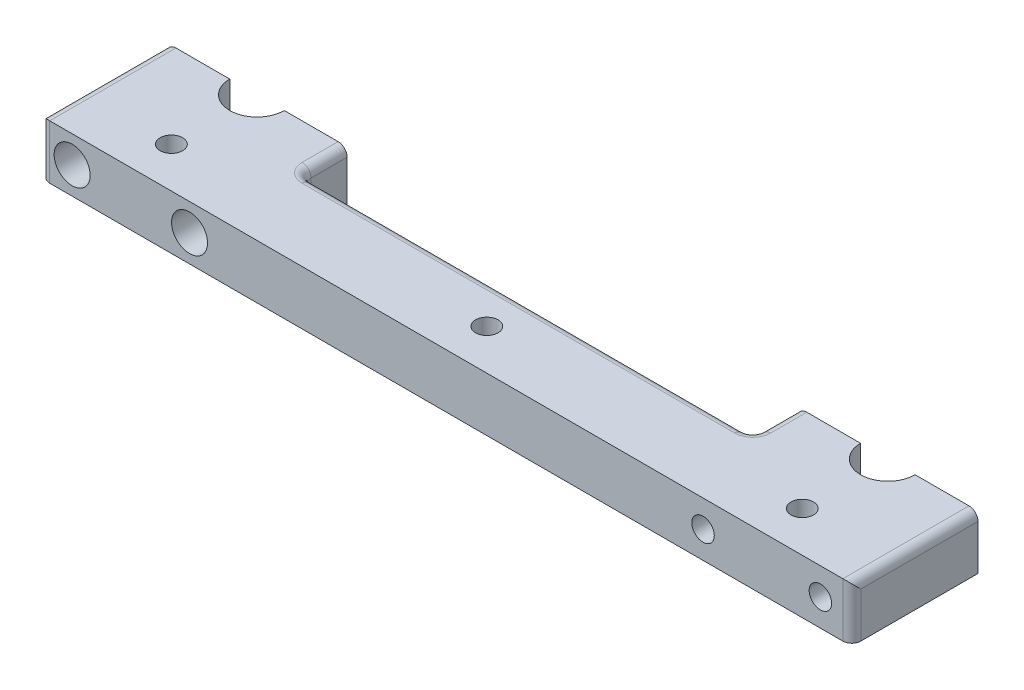
SolidWorks part; units mm, degrees
ref_plane "Plan de face" through (0, 0, 0) normal (0, 0, 1) x (1, 0, 0)
ref_plane "Plan de dessus" through (0, 0, 0) normal (0, 1, 0) x (1, 0, 0)
ref_plane "Plan de droite" through (0, 0, 0) normal (1, 0, 0) x (0, 0, -1)
sketch "Esquisse1" plane through (0, 0, 0) normal (0, 1, 0) x (1, 0, 0)
  line L1 (-85.9777, 19.4021) -> (94.0223, 19.4021)
  line L2 (-85.9777, 19.4021) -> (-85.9777, 37.4021)
  line L3 (-85.9777, 37.4021) -> (94.0223, 37.4021)
  line L4 (94.0223, 19.4021) -> (94.0223, 37.4021)
  dimension "D1" = 180
  dimension "D2" = 18
extrude "Boss.-Extru.1" add sketch "Esquisse1" along normal blind 12
sketch "Esquisse2" plane through (0, 12, 0) normal (0, 1, 0) x (1, 0, 0)
sketch "Esquisse3" plane through (0, 0, -37.4021) normal (0, 0, -1) x (-1, 0, 0)
  line L0 (-94.0223, 0) -> (85.9777, 0) construction
  line L1 (85.9777, 12) -> (45.9777, 12)
  line L2 (85.9777, 12) -> (85.9777, 0)
  line L3 (85.9777, 0) -> (45.9777, 0)
  line L4 (45.9777, 12) -> (45.9777, 0)
  dimension "D1" = 40
extrude "Boss.-Extru.2" add sketch "Esquisse3" along normal blind 10
sketch "Esquisse4" plane through (0, 12, 0) normal (0, 1, 0) x (1, 0, 0)
  line L0 (-85.9777, 47.4021) -> (-45.9777, 47.4021) construction
  circle A0 centre (-65.9777, 47.4021) radius 6.05
  dimension "D1" = 12.1
extrude "Enlèv. mat.-Extru.1" cut sketch "Esquisse4" against normal up to vertex (12 mm away)
sketch "Esquisse5" plane through (0, 0, -47.4021) normal (0, 0, -1) x (-1, 0, 0)
  line L0 (45.9777, 12) -> (59.9277, 0) construction
  line L1 (72.0277, 12) -> (85.9777, 0) construction
  circle A0 centre (52.9527, 6) radius 2.5
  circle A1 centre (79.0027, 6) radius 2.5
  dimension "D1" = 5
extrude "Enlèv. mat.-Extru.2" cut sketch "Esquisse5" against normal up to vertex
sketch "Esquisse6" plane through (0, 0, -19.4021) normal (0, 0, 1) x (1, 0, 0)
  circle A0 centre (-52.9527, 6) radius 4
  circle A1 centre (-79.0027, 6) radius 4
  dimension "D1" = 8
extrude "Enlèv. mat.-Extru.3" cut sketch "Esquisse6" against normal blind 12
ref_plane "Plan2" through (4.0223, 12, -19.4021) normal (-1, 0, 0) x (0, 0, 1)
mirror "Symétrie4" about plane through (4.0223, 12, -19.4021) normal (-1, 0, 0) of "Enlèv. mat.-Extru.2", "Boss.-Extru.2", "Enlèv. mat.-Extru.1"
sketch "Esquisse9" plane through (0, 12, 0) normal (0, 1, 0) x (1, 0, 0)
  line L0 (-85.9777, 28.4021) -> (94.0223, 28.4021) construction
  line L1 (-85.9777, 47.4021) -> (-85.9777, 19.4021) construction
  line L2 (94.0223, 19.4021) -> (94.0223, 47.4021) construction
  line L3 (4.0223, 19.4021) -> (4.0223, 37.4021) construction
  line L4 (-85.9777, 19.4021) -> (94.0223, 19.4021) construction
  line L5 (54.0223, 37.4021) -> (-45.9777, 37.4021) construction
  circle A0 centre (4.0223, 28.4021) radius 2.5
  circle A1 centre (74.0223, 28.4021) radius 2.5
  circle A2 centre (-65.9777, 28.4021) radius 2.5
  arc A3 (-72.0277, 47.4021) -> (-59.9277, 47.4021) centre (-65.9777, 47.4021) ccw construction
  arc A4 (67.9723, 47.4021) -> (80.0723, 47.4021) centre (74.0223, 47.4021) ccw construction
  point P12 (4.0223, 28.4021)
  point P22 (-65.9777, 41.3521)
  point P27 (74.0223, 41.3521)
  dimension "D1" = 5
extrude "Enlèv. mat.-Extru.4" cut sketch "Esquisse9" against normal blind 12
fillet "Congé1" radius 2 9 edges at (94.0223, 6, -19.4021) (-85.9777, 6, -19.4021) (-45.9777, 6, -37.4021) (54.0223, 6, -37.4021) (54.0223, 12, -42.4021) (4.0223, 12, -37.4021) (94.0223, 12, -33.4021) (-45.9777, 12, -42.4021) (-85.9777, 12, -33.4021)
